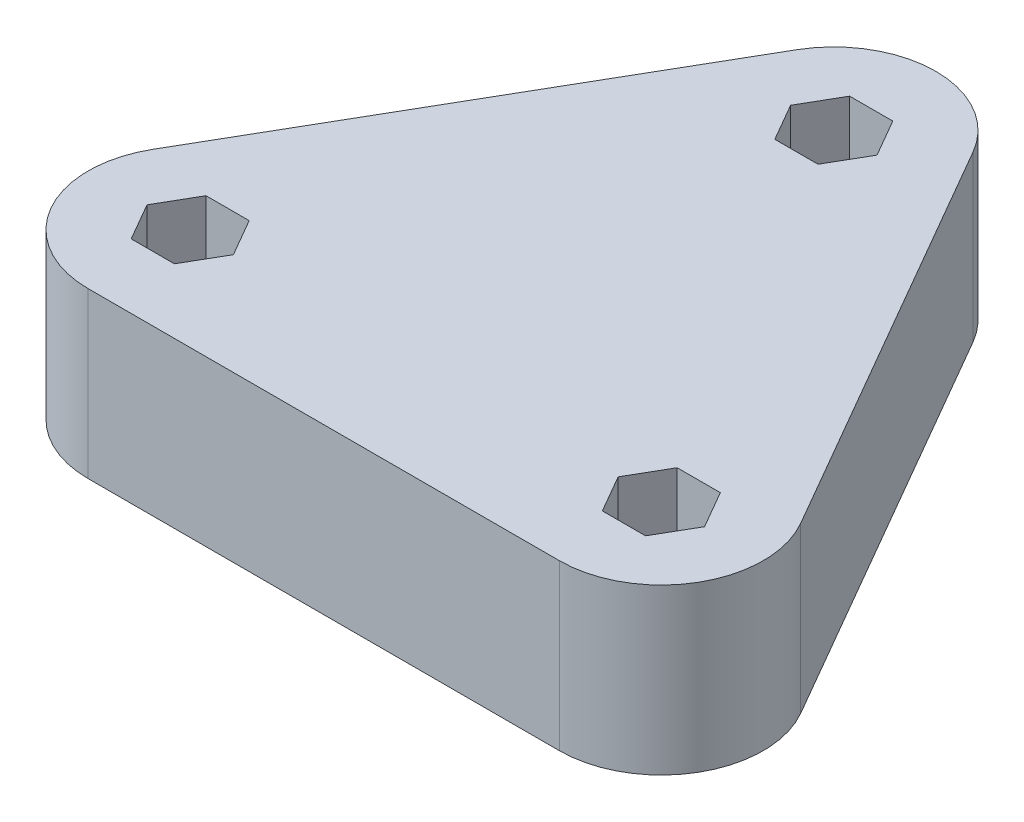
SolidWorks part; units mm, degrees
material "ABS"
ref_plane "Plan de face" through (0, 0, 0) normal (0, 0, 1) x (1, 0, 0)
ref_plane "Plan de dessus" through (0, 0, 0) normal (0, 1, 0) x (1, 0, 0)
ref_plane "Plan de droite" through (0, 0, 0) normal (1, 0, 0) x (0, 0, -1)
sketch "Esquisse1" plane through (0, 0, 0) normal (0, 1, 0) x (1, 0, 0)
  line L0 (-6.4952, 23.75) -> (-23.8157, -6.25)
  line L1 (-17.3205, -17.5) -> (17.3205, -17.5)
  line L2 (6.4952, 23.75) -> (23.8157, -6.25)
  line L3 (0, 20) -> (0, 0) construction
  line L4 (0, 0) -> (-17.3205, -10) construction
  line L6 (17.3205, -10) -> (0, 0) construction
  circle A0 centre (0, 0) radius 11.9
  circle A1 centre (-17.3205, -10) radius 2
  arc A2 (-23.8157, -6.25) -> (-17.3205, -17.5) centre (-17.3205, -10) ccw
  circle A3 centre (0, 20) radius 2
  circle A4 centre (17.3205, -10) radius 2
  circle A5 centre (0, 0) radius 16 construction
  arc A6 (17.3205, -17.5) -> (23.8157, -6.25) centre (17.3205, -10) ccw
  arc A7 (6.4952, 23.75) -> (-6.4952, 23.75) centre (0, 20) ccw
  circle A8 centre (0, 20) radius 4 construction
  dimension "D1" = 23.8
  dimension "D2" = 4
  dimension "D3" = 32
  dimension "D4" = 120
  dimension "D6" = 49.641
  dimension "D8" = 7.5
  dimension "D9" = 20
  dimension "D10" = 8
  dimension "D5" = 17.5
  dimension "D7" = 45
extrude "Boss.-Extru.1" add sketch "Esquisse1" along normal blind 12
sketch "Esquisse2" plane through (0, 12, 0) normal (0, 1, 0) x (1, 0, 0)
  line L0 (23.8157, -6.25) -> (6.4952, 23.75) construction
  line L1 (-18.9082, -7.25) -> (-20.4959, -10)
  line L2 (-20.4959, -10) -> (-18.9082, -12.75)
  line L3 (-18.9082, -12.75) -> (-15.7328, -12.75)
  line L4 (-15.7328, -12.75) -> (-14.1451, -10)
  line L5 (-14.1451, -10) -> (-15.7328, -7.25)
  line L6 (-15.7328, -7.25) -> (-18.9082, -7.25)
  line L7 (-1.5877, 22.75) -> (-3.1754, 20)
  line L8 (-3.1754, 20) -> (-1.5877, 17.25)
  line L9 (-1.5877, 17.25) -> (1.5877, 17.25)
  line L10 (1.5877, 17.25) -> (3.1754, 20)
  line L11 (3.1754, 20) -> (1.5877, 22.75)
  line L12 (1.5877, 22.75) -> (-1.5877, 22.75)
  line L13 (18.9082, -7.25) -> (15.7328, -7.25)
  line L14 (15.7328, -7.25) -> (14.1451, -10)
  line L15 (14.1451, -10) -> (15.7328, -12.75)
  line L16 (15.7328, -12.75) -> (18.9082, -12.75)
  line L17 (18.9082, -12.75) -> (20.4959, -10)
  line L18 (20.4959, -10) -> (18.9082, -7.25)
  line L19 (-6.4952, 23.75) -> (-23.8157, -6.25) construction
  circle A0 centre (-17.3205, -10) radius 2.75 construction
  circle A1 centre (0, 20) radius 2.75 construction
  circle A2 centre (17.3205, -10) radius 2.75 construction
  dimension "D1" = 5.5
extrude "Enlèv. mat.-Extru.1" cut sketch "Esquisse2" against normal blind 5
sketch "Sketch1" plane through (0, 12, 0) normal (0, 1, 0) x (1, 0, 0)
  circle A0 centre (0, 0) radius 11.9 construction
  circle A1 centre (0, 0) radius 11.9
extrude "Boss-Extrude1" add sketch "Sketch1" against normal blind 2 separate body
sketch "Sketch2" plane through (0, 0, 0) normal (0, -1, 0) x (1, 0, 0)
  circle A0 centre (0, 0) radius 11.9
  circle A1 centre (0, 0) radius 15.5
extrude "Boss-Extrude2" add sketch "Sketch2" along normal blind 1.5
sketch "Sketch3" plane through (0, 12, 0) normal (0, 1, 0) x (1, 0, 0)
  line L0 (-1.5877, 22.75) -> (-3.1754, 20) construction
  line L1 (-3.1754, 20) -> (-1.5877, 17.25) construction
  line L2 (-1.5877, 17.25) -> (1.5877, 17.25) construction
  line L3 (-6.4952, 23.75) -> (-23.8157, -6.25)
  line L4 (-17.3205, -17.5) -> (17.3205, -17.5)
  line L5 (23.8157, -6.25) -> (6.4952, 23.75)
  line L6 (-6.4952, 23.75) -> (-23.8157, -6.25)
  line L7 (-17.3205, -17.5) -> (17.3205, -17.5)
  line L8 (23.8157, -6.25) -> (6.4952, 23.75)
  line L9 (1.5877, 17.25) -> (3.1754, 20) construction
  line L10 (3.1754, 20) -> (1.5877, 22.75) construction
  line L11 (1.5877, 22.75) -> (-1.5877, 22.75) construction
  line L12 (18.9082, -12.75) -> (20.4959, -10) construction
  line L13 (14.1451, -10) -> (15.7328, -12.75) construction
  line L14 (15.7328, -12.75) -> (18.9082, -12.75) construction
  line L15 (20.4959, -10) -> (18.9082, -7.25) construction
  line L16 (18.9082, -7.25) -> (15.7328, -7.25) construction
  line L17 (15.7328, -7.25) -> (14.1451, -10) construction
  line L18 (-18.9082, -7.25) -> (-20.4959, -10) construction
  line L19 (-20.4959, -10) -> (-18.9082, -12.75) construction
  line L20 (-18.9082, -12.75) -> (-15.7328, -12.75) construction
  line L21 (-15.7328, -12.75) -> (-14.1451, -10) construction
  line L22 (-14.1451, -10) -> (-15.7328, -7.25) construction
  line L23 (-15.7328, -7.25) -> (-18.9082, -7.25) construction
  line L24 (-1.5877, 22.75) -> (-3.1754, 20)
  line L25 (-3.1754, 20) -> (-1.5877, 17.25)
  line L26 (-1.5877, 17.25) -> (1.5877, 17.25)
  line L27 (1.5877, 17.25) -> (3.1754, 20)
  line L28 (3.1754, 20) -> (1.5877, 22.75)
  line L29 (1.5877, 22.75) -> (-1.5877, 22.75)
  line L30 (18.9082, -12.75) -> (20.4959, -10)
  line L31 (14.1451, -10) -> (15.7328, -12.75)
  line L32 (15.7328, -12.75) -> (18.9082, -12.75)
  line L33 (20.4959, -10) -> (18.9082, -7.25)
  line L34 (18.9082, -7.25) -> (15.7328, -7.25)
  line L35 (15.7328, -7.25) -> (14.1451, -10)
  line L36 (-18.9082, -7.25) -> (-20.4959, -10)
  line L37 (-20.4959, -10) -> (-18.9082, -12.75)
  line L38 (-18.9082, -12.75) -> (-15.7328, -12.75)
  line L39 (-15.7328, -12.75) -> (-14.1451, -10)
  line L40 (-14.1451, -10) -> (-15.7328, -7.25)
  line L41 (-15.7328, -7.25) -> (-18.9082, -7.25)
  arc A3 (6.4952, 23.75) -> (-6.4952, 23.75) centre (0, 20) ccw
  arc A4 (-23.8157, -6.25) -> (-17.3205, -17.5) centre (-17.3205, -10) ccw
  arc A5 (17.3205, -17.5) -> (23.8157, -6.25) centre (17.3205, -10) ccw
  arc A6 (6.4952, 23.75) -> (-6.4952, 23.75) centre (0, 20) ccw
  arc A7 (-23.8157, -6.25) -> (-17.3205, -17.5) centre (-17.3205, -10) ccw
  arc A8 (17.3205, -17.5) -> (23.8157, -6.25) centre (17.3205, -10) ccw
  dimension "D1" = 0
extrude "Boss-Extrude3" add sketch "Sketch3" along normal blind 0.1
